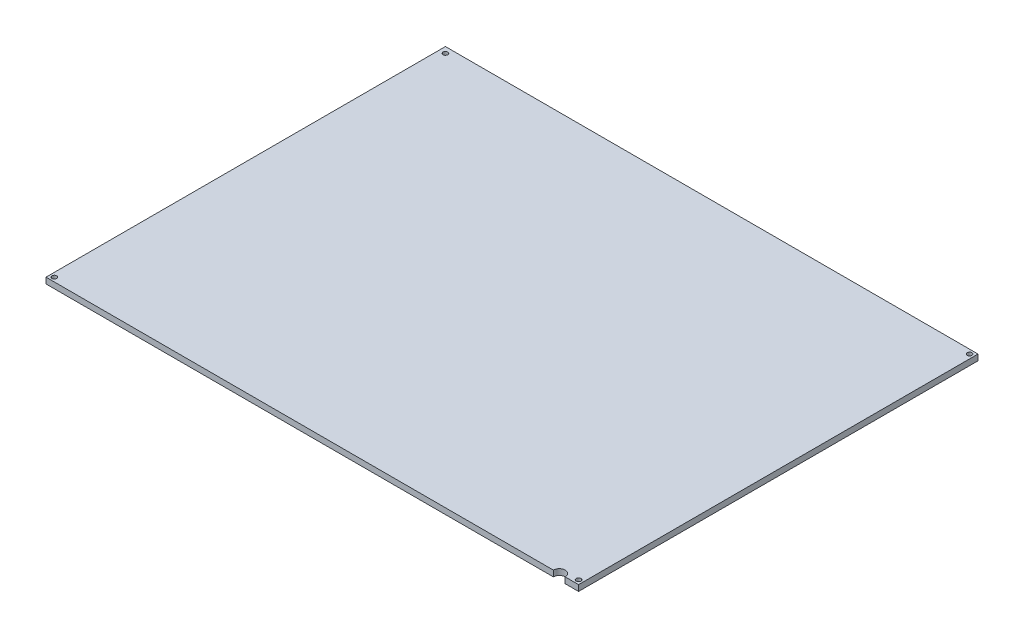
SolidWorks part; units mm, degrees
ref_plane "Front Plane" through (0, 0, 0) normal (0, 0, 1) x (1, 0, 0)
ref_plane "Top Plane" through (0, 0, 0) normal (0, 1, 0) x (1, 0, 0)
ref_plane "Right Plane" through (0, 0, 0) normal (1, 0, 0) x (0, 0, -1)
sketch "Sketch1" plane through (0, 0, 0) normal (0, 1, 0) x (1, 0, 0)
  line L1 (-450, 337.5) -> (450, 337.5)
  line L2 (-450, 337.5) -> (-450, -337.5)
  line L3 (-450, -337.5) -> (450, -337.5)
  line L4 (450, 337.5) -> (450, -337.5)
  line L5 (-450, 337.5) -> (450, -337.5) construction
  line L6 (-450, -337.5) -> (450, 337.5) construction
  point P0 (0, 0)
extrude "Boss-Extrude1" add sketch "Sketch1" along normal blind 10
sketch "Sketch2" plane through (0, 10, 0) normal (0, 1, 0) x (1, 0, 0)
  line L0 (-450, 337.5) -> (-430, 317.5) construction
  line L1 (-430, 337.5) -> (-450, 317.5) construction
  line L2 (-450, 337.5) -> (-430, 337.5) construction
  line L3 (450, 337.5) -> (-450, 337.5) construction
  line L5 (-450, 337.5) -> (-430, 337.5)
  line L6 (-450, 337.5) -> (-450, 317.5)
  line L7 (-450, 317.5) -> (-430, 317.5)
  line L8 (-430, 337.5) -> (-430, 317.5)
sketch "Sketch3" plane through (0, 10, 0) normal (0, 1, 0) x (1, 0, 0)
  line L0 (-450, 337.5) -> (-430, 317.5) construction
  circle A0 centre (-440, 327.5) radius 4
extrude "Cut-Extrude1" cut sketch "Sketch3" against normal blind 10
sketch "Sketch4" plane through (0, 10, 0) normal (0, 1, 0) x (1, 0, 0)
  line L0 (-450, -337.5) -> (-435.8579, -323.3579) construction
  circle A0 centre (-442.9289, -330.4289) radius 4
extrude "Cut-Extrude2" cut sketch "Sketch4" against normal blind 10
sketch "Sketch5" plane through (0, 10, 0) normal (0, 1, 0) x (1, 0, 0)
  line L0 (450, 337.5) -> (435.8579, 323.3579) construction
  circle A0 centre (442.9289, 330.4289) radius 4
extrude "Cut-Extrude3" cut sketch "Sketch5" against normal blind 10
sketch "Sketch6" plane through (0, 10, 0) normal (0, 1, 0) x (1, 0, 0)
  line L0 (450, -337.5) -> (435.8579, -323.3579) construction
  circle A0 centre (442.9289, -330.4289) radius 4
extrude "Cut-Extrude4" cut sketch "Sketch6" against normal blind 10
sketch "Sketch7" plane through (0, 10, 0) normal (0, 1, 0) x (1, 0, 0)
  line L0 (-450, -337.5) -> (450, -337.5) construction
  circle A0 centre (417.3833, -337.5) radius 10
extrude "Cut-Extrude5" cut sketch "Sketch7" against normal blind 10
